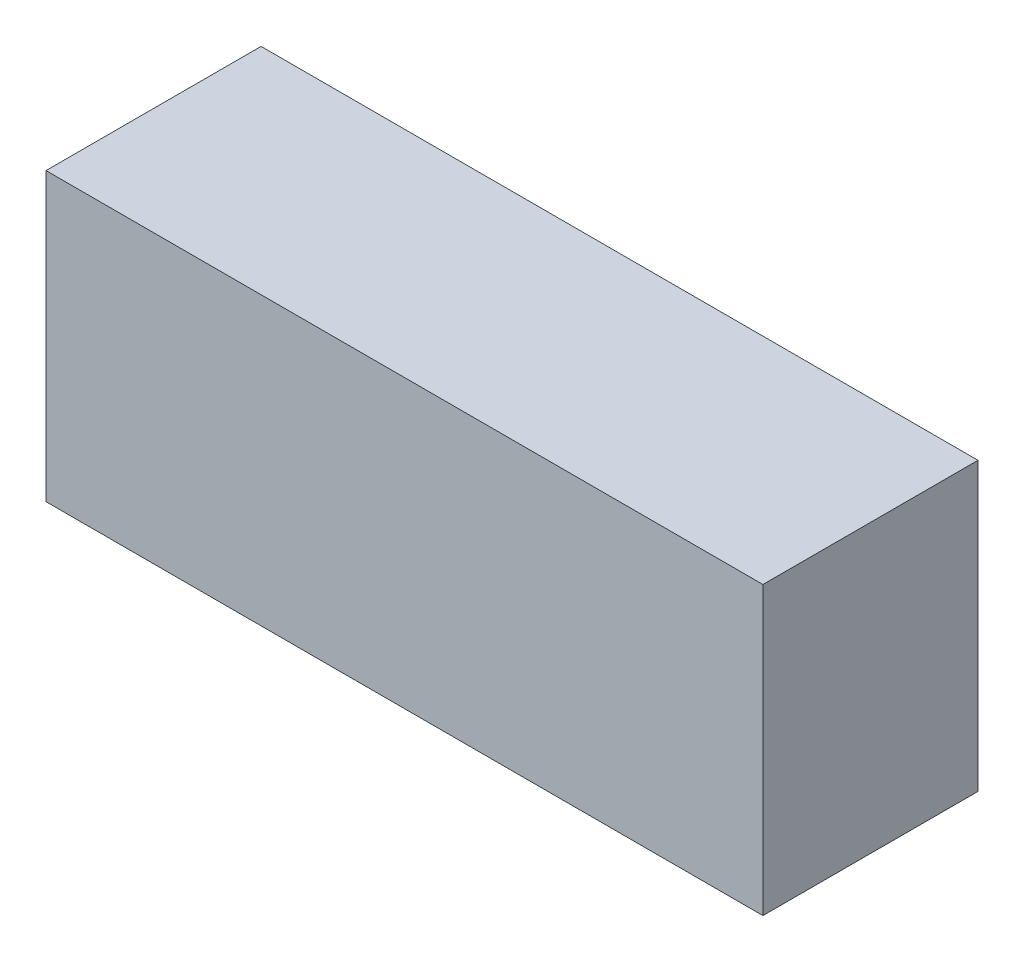
SolidWorks part; units mm, degrees
ref_plane "Front Plane" through (0, 0, 0) normal (0, 0, 1) x (1, 0, 0)
ref_plane "Top Plane" through (0, 0, 0) normal (0, 1, 0) x (1, 0, 0)
ref_plane "Right Plane" through (0, 0, 0) normal (1, 0, 0) x (0, 0, -1)
sketch "Sketch1" plane through (0, 0, 0) normal (0, 1, 0) x (1, 0, 0)
  line L1 (50, -15) -> (-50, -15)
  line L2 (50, -15) -> (50, 15)
  line L3 (50, 15) -> (-50, 15)
  line L4 (-50, -15) -> (-50, 15)
  line L5 (50, -15) -> (-50, 15) construction
  line L6 (50, 15) -> (-50, -15) construction
  point P0 (0, 0)
  dimension "D1" = 100
  dimension "D2" = 30
extrude "Boss-Extrude1" add sketch "Sketch1" along normal mid plane 40
